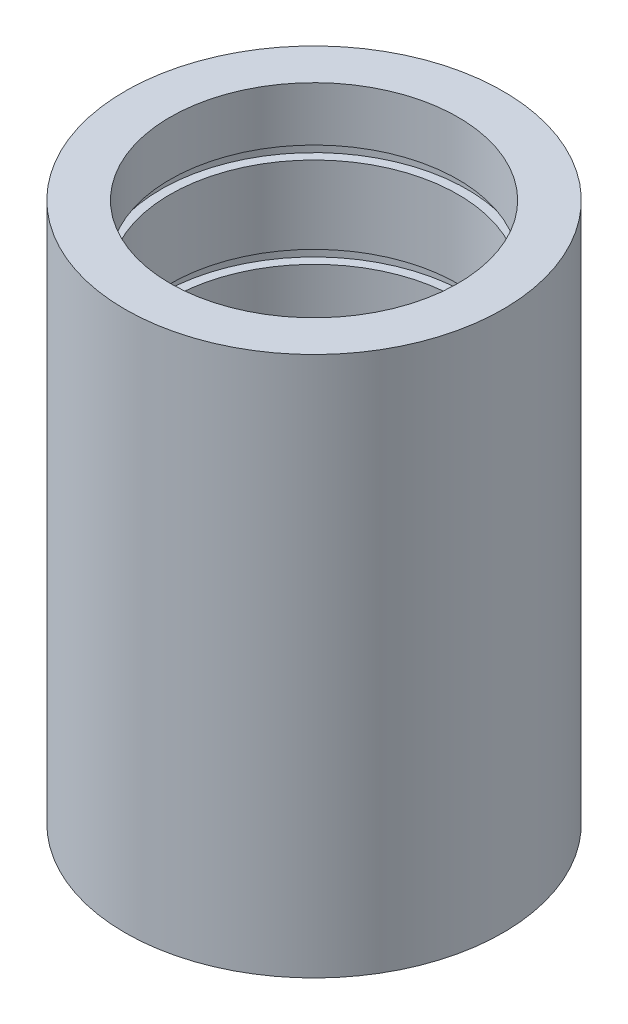
SolidWorks part; units mm, degrees
ref_plane "Front Plane" through (0, 0, 0) normal (0, 0, 1) x (1, 0, 0)
ref_plane "Top Plane" through (0, 0, 0) normal (0, 1, 0) x (1, 0, 0)
ref_plane "Right Plane" through (0, 0, 0) normal (1, 0, 0) x (0, 0, -1)
sketch "Sketch1" plane through (0, 0, 0) normal (0, 1, 0) x (1, 0, 0)
  circle A1 centre (0, 0) radius 40
  circle A2 centre (0, 0) radius 52.5
  dimension "D1" = 105
  dimension "D2" = 80
extrude "Boss-Extrude1" add sketch "Sketch1" along normal blind 150 contours A2 A1
ref_plane "Ylin ura yläreuna" through (0, 135, 0) normal (0, 1, 0) x (1, 0, 0)
ref_plane "2. ylin ura yläreuna" through (0, 109.9, 0) normal (0, 1, 0) x (1, 0, 0)
sketch "Sketch7" plane through (0, 135, 0) normal (0, 1, 0) x (1, 0, 0)
  circle A0 centre (0, 0) radius 42.5
extrude "Ylin ura" cut sketch "Sketch7" against normal blind 3.6
sketch "Sketch8" plane through (0, 109.9, 0) normal (0, 1, 0) x (1, 0, 0)
  circle A0 centre (0, 0) radius 42.5
extrude "Toka ylin ura" cut sketch "Sketch8" against normal blind 3.6
ref_plane "Alin ura yläreuna" through (0, 28.6, 0) normal (0, -1, 0) x (-1, 0, 0)
ref_plane "Toka alin ura yläreuna" through (0, 50.1, 0) normal (0, -1, 0) x (-1, 0, 0)
sketch "Sketch9" plane through (0, 28.6, 0) normal (0, -1, 0) x (-1, 0, 0)
  circle A0 centre (0, 0) radius 42.5
extrude "Cut-Extrude4" [suppressed] cut sketch "Sketch9" along normal blind 3.6
sketch "Sketch10" plane through (0, 50.1, 0) normal (0, -1, 0) x (-1, 0, 0)
  circle A0 centre (0, 0) radius 42.5
extrude "Cut-Extrude5" cut sketch "Sketch10" against normal blind 3.6
sketch "Sketch13" plane through (0, 0, 0) normal (0, -1, 0) x (-1, 0, 0)
  line L0 (0, -52.5) -> (0, -40) construction
  line L1 (0, -40) -> (0, -46.25) construction
  circle A1 centre (0, 0) radius 52.5 construction
  circle A2 centre (0, 0) radius 40 construction
  circle A3 centre (0, 0) radius 46.25 construction
hole_wizard "Ø8.0mm Dowel Hole1" positions "Sketch14" profile "Sketch15" hole size "Ø8.0" standard "ISO"
sketch "Sketch14" plane through (0, 0, 0) normal (0, -1, 0) x (-1, 0, 0)
  point P0 (0, -46.25)
  point P8 (-40.0537, -23.125)
  point P9 (-40.0537, 23.125)
  point P10 (0, 46.25)
  point P11 (40.0537, 23.125)
  point P12 (40.0537, -23.125)
  dimension "D1" = 6
sketch "Sketch15" plane through (0, 0, 46.25) normal (1, 0, 0) x (0, 0, -1)
  line L0 (0, 0) -> (0, 25)
  line L1 (0, 25) -> (4, 22.5966)
  line L2 (4, 22.5966) -> (4, 0.025)
  line L3 (4, 0.025) -> (4.025, 0)
  line L5 (4.025, 0) -> (0, 0)
  line L6 (-4, 0.025) -> (-4.025, 0) construction
  line L10 (0, 25) -> (-4, 22.5966) construction
  line L11 (0, -6.35) -> (0, 107.95) construction
  dimension "Hole Dia." = 8
  dimension "Hole Depth" = 25
  dimension "Near C'Sink Dia." = 8.05
  dimension "Near C'Sink Angle" = 90
  dimension "Drill Angle" = 118
